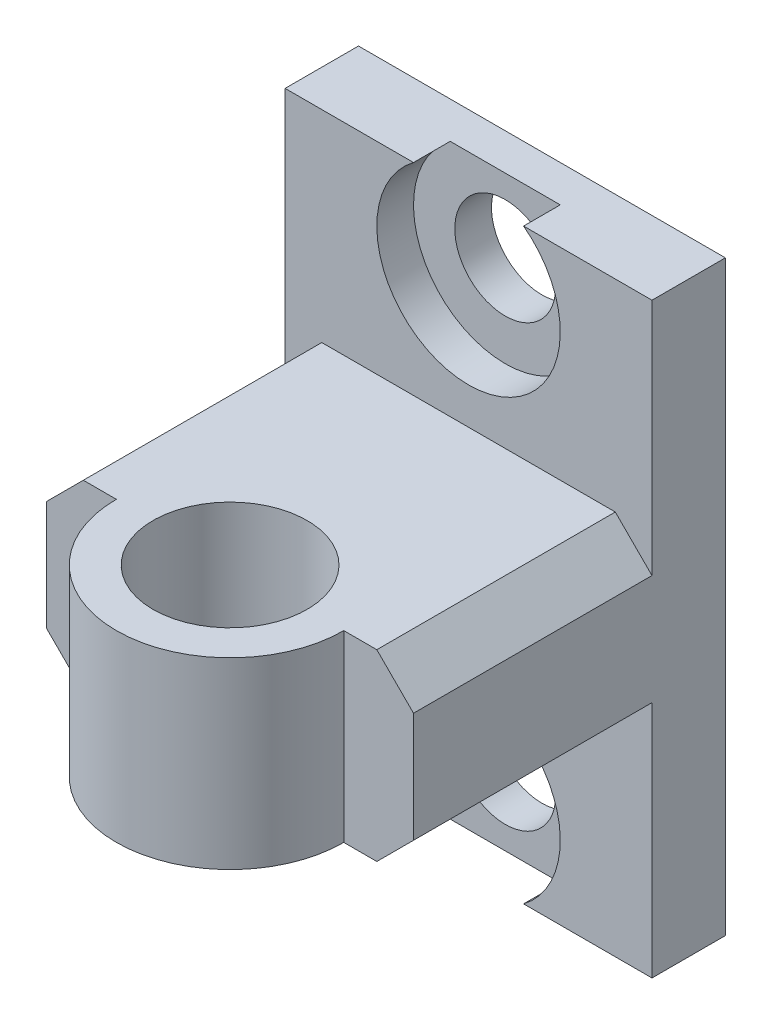
SolidWorks part; units mm, degrees
ref_plane "前视基准面" through (0, 0, 0) normal (0, 0, 1) x (1, 0, 0)
ref_plane "上视基准面" through (0, 0, 0) normal (0, 1, 0) x (1, 0, 0)
ref_plane "右视基准面" through (0, 0, 0) normal (1, 0, 0) x (0, 0, -1)
sketch "草图1" plane through (0, 0, 0) normal (0, 0, 1) x (1, 0, 0)
  line L0 (10, 0) -> (10, -32) construction
  line L1 (0, 0) -> (20, 0)
  line L2 (0, 0) -> (0, -32)
  line L3 (0, -32) -> (20, -32)
  line L4 (20, 0) -> (20, -32)
  circle A0 centre (10, -4) radius 2.75
  circle A1 centre (10, -28) radius 2.75
  point P11 (20, -16)
  dimension "D3" = 5.5
  dimension "D4" = 5.5
  dimension "D5" = 24
  dimension "D6" = 12
  dimension "D7" = 10
  dimension "D1" = 32
  dimension "D2" = 20
extrude "凸台-拉伸1" add sketch "草图1" along normal blind 4
sketch "草图2" plane through (0, 0, 4) normal (0, 0, 1) x (1, 0, 0)
  line L0 (0, 0) -> (0, -32) construction
  line L1 (0, -11) -> (20, -11)
  line L2 (0, -11) -> (0, -21)
  line L3 (0, -21) -> (20, -21)
  line L4 (20, -11) -> (20, -21)
  line L5 (20, -32) -> (20, 0) construction
  line L6 (20, 0) -> (0, 0) construction
  dimension "D1" = 10
  dimension "D2" = 11
extrude "凸台-拉伸2" add sketch "草图2" along normal blind 13
sketch "草图4" plane through (0, -21, 0) normal (0, -1, 0) x (1, 0, 0)
  line L0 (0, 17) -> (20, 17) construction
  circle A0 centre (10, 17) radius 6.2
  dimension "D1" = 12.4
extrude "凸台-拉伸3" add sketch "草图4" against normal up to surface (10 mm away) up to face at (10, -11, 10.5)
sketch "草图5" plane through (0, -11, 0) normal (0, 1, 0) x (1, 0, 0)
  circle A0 centre (10, -17) radius 4.2
  dimension "D1" = 8.4
extrude "切除-拉伸1" cut sketch "草图5" against normal blind 13
chamfer "倒角1" distance 2 angle 45 4 edges at (20, -11, 10.5) (20, -21, 10.5) (0, -21, 10.5) (0, -11, 10.5)
sketch "草图6" plane through (0, 0, 4) normal (0, 0, 1) x (1, 0, 0)
  circle A0 centre (10, -28) radius 5
  circle A1 centre (10, -4) radius 5
  dimension "D1" = 10
  dimension "D2" = 10
extrude "切除-拉伸2" cut sketch "草图6" against normal blind 2
